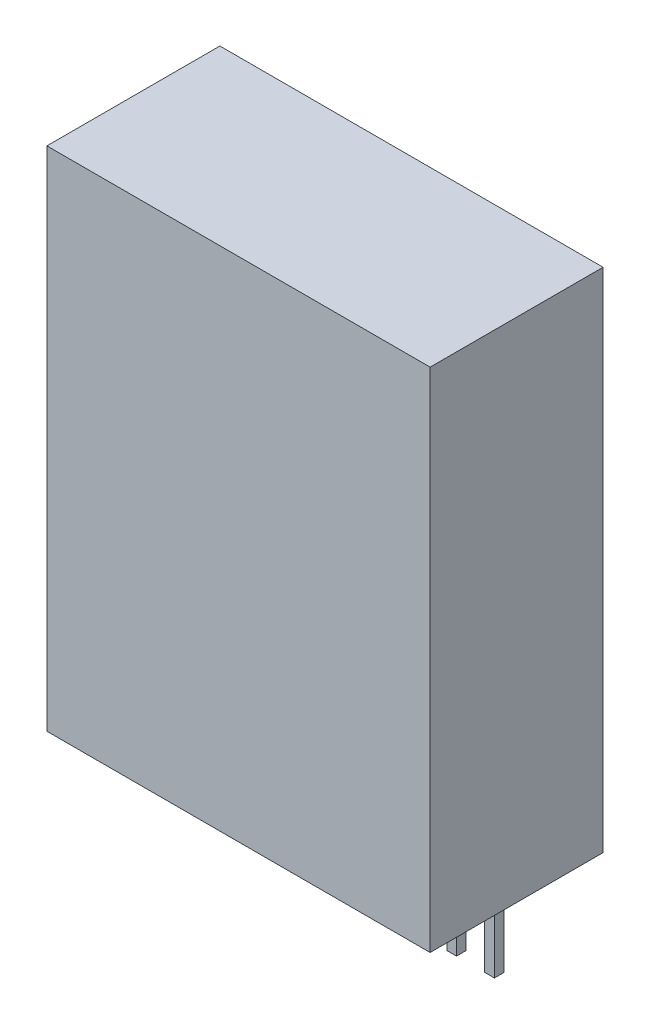
SolidWorks part; units mm, degrees
ref_plane "Plan de face" through (0, 0, 0) normal (0, 0, 1) x (1, 0, 0)
ref_plane "Plan de dessus" through (0, 0, 0) normal (0, 1, 0) x (1, 0, 0)
ref_plane "Plan de droite" through (0, 0, 0) normal (1, 0, 0) x (0, 0, -1)
sketch "Esquisse1" plane through (0, 0, 0) normal (0, 0, 1) x (1, 0, 0)
  line L1 (-12.85, 17) -> (12.85, 17)
  line L2 (-12.85, 17) -> (-12.85, -17)
  line L3 (-12.85, -17) -> (12.85, -17)
  line L4 (12.85, 17) -> (12.85, -17)
  point P4 (0, 17)
  point P6 (-12.85, 0)
  dimension "D1" = 25.7
  dimension "D2" = 34
extrude "Boss.-Extru.1" add sketch "Esquisse1" along normal mid plane 11.6
sketch "Esquisse2" plane through (0, -17, 0) normal (0, -1, 0) x (1, 0, 0)
  line L2 (-0.325, -0.875) -> (0.325, -0.875)
  line L3 (-0.325, -0.875) -> (-0.325, -1.525)
  line L4 (-0.325, -1.525) -> (0.325, -1.525)
  line L5 (0.325, -0.875) -> (0.325, -1.525)
  line L6 (-12.85, -5.8) -> (12.85, -5.8) construction
  point P6 (0, -1.525)
  point P7 (-0.325, -1.2)
  dimension "D1" = 0.65
  dimension "D3" = 4.6
extrude "Boss.-Extru.2" add sketch "Esquisse2" along normal blind 6
pattern_linear "Répétition linéaire1" count 5 spacing 2.54 along (1, 0, 0) count 5 spacing 2.54 along (-1, 0, 0) of "Boss.-Extru.2"
